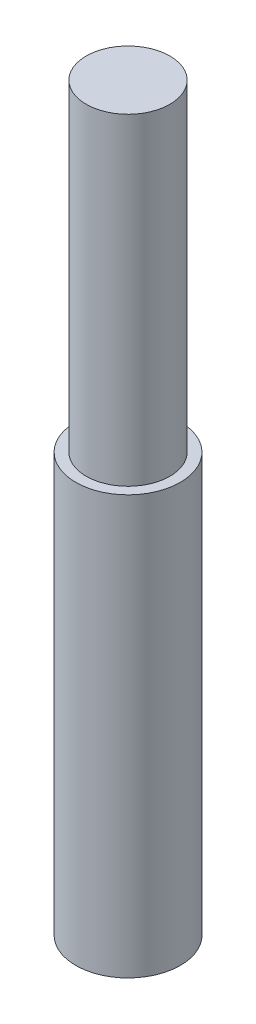
SolidWorks part; units mm, degrees
ref_plane "Ön Düzlem" through (0, 0, 0) normal (0, 0, 1) x (1, 0, 0)
ref_plane "Üst Düzlem" through (0, 0, 0) normal (0, 1, 0) x (1, 0, 0)
ref_plane "Sağ Düzlem" through (0, 0, 0) normal (1, 0, 0) x (0, 0, -1)
sketch "Çizim1" plane through (0, 0, 0) normal (0, 0, 1) x (1, 0, 0)
  line L0 (0, 0) -> (0, 35.4)
  line L1 (0, 35.4) -> (2, 35.4)
  line L2 (2, 35.4) -> (2, 20)
  line L3 (2, 20) -> (2.5, 20)
  line L4 (2.5, 20) -> (2.5, 0)
  line L5 (2.5, 0) -> (0, 0)
  line L7 (10, 28.4) -> (-10, 28.4) construction
  point P3 (2, 28.4)
  dimension "D1" = 7
  dimension "D2" = 2
  dimension "D3" = 2.5
  dimension "D4" = 20
revolve "Döndür1" add sketch "Çizim1" angle 360 about L0
sketch "Çizim2" plane through (0, 0, 0) normal (0, -1, 0) x (1, 0, 0)
  circle A0 centre (0, 0) radius 2
  dimension "D1" = 4
extrude "Kes-Ekstrüzyon1" cut sketch "Çizim2" against normal blind 10
fillet "Radyus1" radius 0.4 1 edges at (0, 0, -2)
